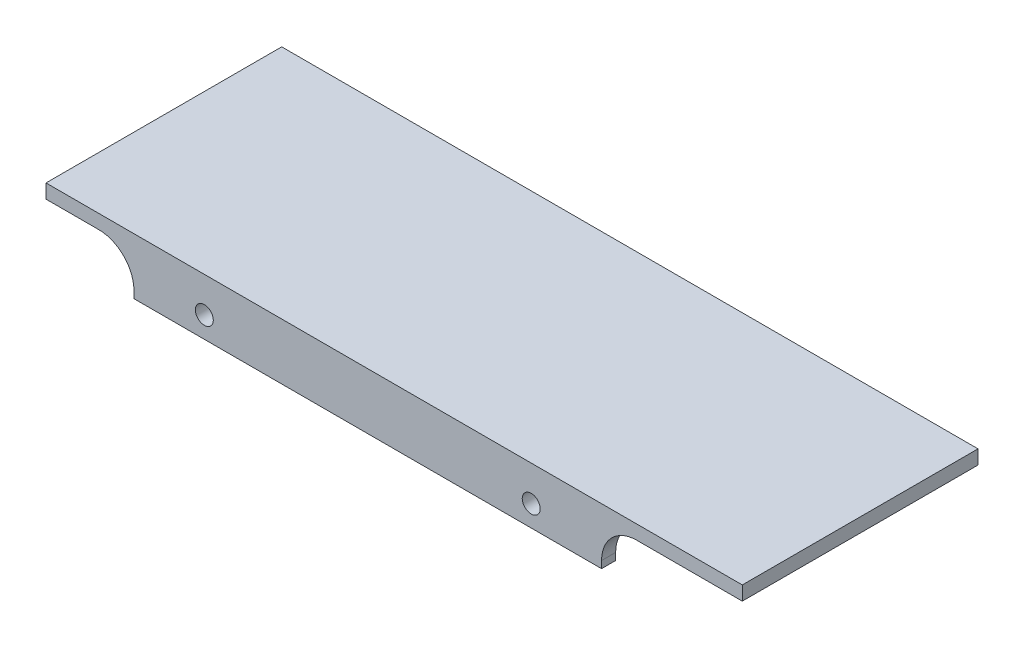
SolidWorks part; units mm, degrees
ref_plane "Front Plane" through (0, 0, 0) normal (0, 0, 1) x (1, 0, 0)
ref_plane "Top Plane" through (0, 0, 0) normal (0, 1, 0) x (1, 0, 0)
ref_plane "Right Plane" through (0, 0, 0) normal (1, 0, 0) x (0, 0, -1)
sketch "Sketch1" plane through (0, 0, 0) normal (0, 0, 1) x (1, 0, 0)
  line L1 (-182.9174, 55.8) -> (-50, 55.8)
  line L2 (-182.9174, 55.8) -> (-182.9174, 43.8)
  line L3 (-182.9174, 43.8) -> (-50, 43.8)
  line L4 (-50, 55.8) -> (-50, 43.8)
  line L5 (-182.9174, 0) -> (-182.9174, 55.8) construction
  line L6 (-50, -0.2) -> (-50, 55.8) construction
  line L7 (-182.9174, 27.9) -> (-50, 27.8) construction
  line L8 (-116.4587, 27.85) -> (-116.4587, 55.8) construction
  line L9 (-207.9174, 59.8) -> (-10, 59.8) construction
  circle A0 centre (-162.9174, 49.8) radius 2.55
  circle A1 centre (-70, 49.8) radius 2.55
  point P19 (0, 0)
  point P20 (-182.9174, 49.8)
  point P21 (0, 0)
  point P22 (0, 0)
  dimension "D2" = 20
  dimension "D4" = 5.1
  dimension "D5" = 5.1
  dimension "D1" = 12
  dimension "D3" = 20
  dimension "D6" = 4
extrude "Boss-Extrude1" add sketch "Sketch1" along normal blind 4
sketch "Sketch2" plane through (0, 55.8, 0) normal (0, 1, 0) x (1, 0, 0)
  line L1 (-332.9174, -67) -> (25, -67) construction
  line L2 (-207.9174, 0) -> (-10, 0)
  line L3 (-207.9174, 0) -> (-207.9174, -67)
  line L4 (-207.9174, -67) -> (-10, -67)
  line L5 (-10, 0) -> (-10, -67)
  line L6 (-10, 0) -> (-10, 4) construction
extrude "Boss-Extrude2" add sketch "Sketch2" along normal blind 4
sketch "Sketch3" plane through (0, 0, 67) normal (0, 0, -1) x (-1, 0, 0)
  line L4 (182.9174, 43.8) -> (182.9174, 55.8)
  line L5 (50, 43.8) -> (182.9174, 43.8)
  line L6 (50, 55.8) -> (50, 43.8)
  line L7 (182.9174, 55.8) -> (50, 55.8)
  line L8 (182.9174, 43.8) -> (182.9174, 55.8)
  line L9 (50, 43.8) -> (182.9174, 43.8)
  line L10 (50, 55.8) -> (50, 43.8)
  line L11 (182.9174, 55.8) -> (50, 55.8)
  circle A0 centre (162.9174, 49.8) radius 2.55 construction
  circle A1 centre (70, 49.8) radius 2.55 construction
  circle A2 centre (162.9174, 49.8) radius 2.55
  circle A3 centre (70, 49.8) radius 2.55
  dimension "D1" = 0
extrude "Boss-Extrude3" add sketch "Sketch3" along normal blind 4
fillet "Fillet1" radius 10 4 edges at (-182.9174, 55.8, 2) (-182.9174, 55.8, 65) (-50, 55.8, 2) (-50, 55.8, 65)
fillet "Fillet2" radius 2.5 2 edges at (-116.4587, 55.8, 63) (-116.4587, 55.8, 4)
